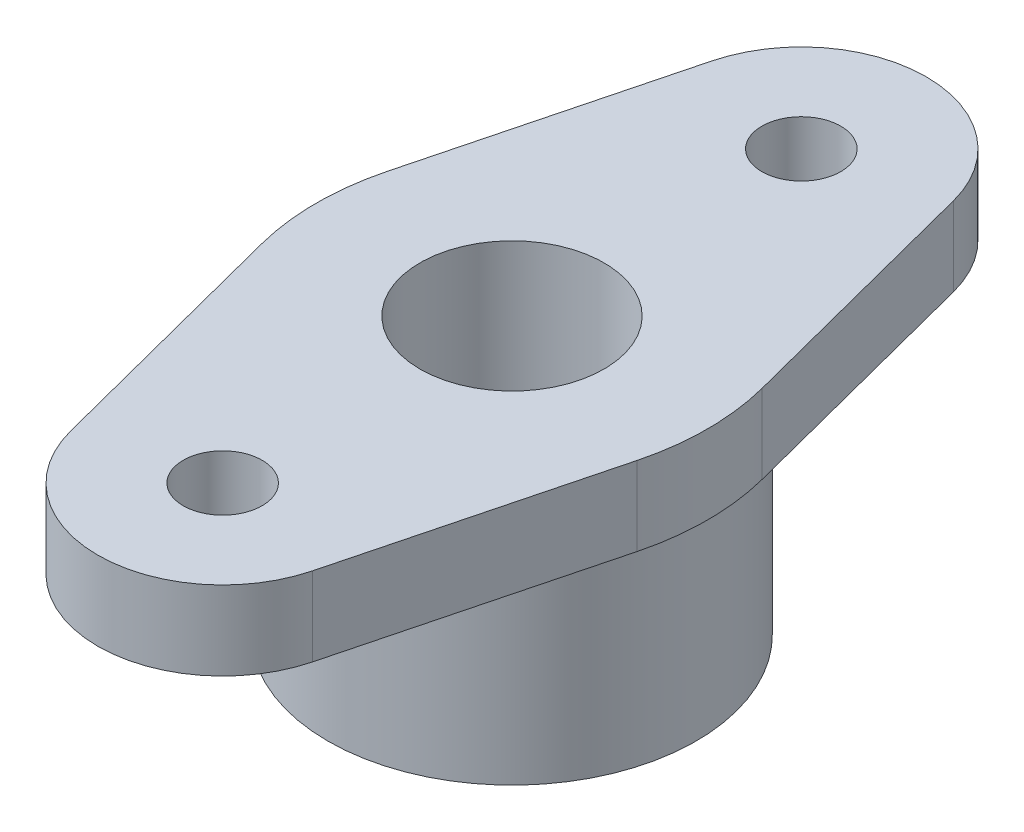
SolidWorks part; units mm, degrees
ref_plane "Front Plane" through (0, 0, 0) normal (0, 0, 1) x (1, 0, 0)
ref_plane "Top Plane" through (0, 0, 0) normal (0, 1, 0) x (1, 0, 0)
ref_plane "Right Plane" through (0, 0, 0) normal (1, 0, 0) x (0, 0, -1)
sketch "Sketch2" plane through (0, 0, 0) normal (0, 1, 0) x (1, 0, 0)
  line L0 (-31, 0) -> (31, 0) construction
  line L1 (0, 0) -> (0, 44) construction
  line L2 (18.3952, 48.7557) -> (31, 0)
  line L3 (31, 0) -> (18.3952, -48.7557)
  line L4 (-31, 0) -> (-18.3952, -48.7557)
  line L5 (-18.3952, 48.7557) -> (-31, 0)
  circle A0 centre (0, 44) radius 19
  circle A1 centre (0, 44) radius 6
  circle A2 centre (0, 0) radius 14
  circle A3 centre (0, -44) radius 6
  circle A4 centre (0, -44) radius 19
  dimension "D1" = 38
  dimension "D2" = 12
  dimension "D3" = 28
  dimension "D4" = 88
  dimension "D5" = 62
extrude "Boss-Extrude1" add sketch "Sketch2" along normal blind 12 contours L4 A4 L3 L2 A0 L5 A2 | A4 A3 | A0 A1
fillet "Fillet1" radius 38 2 edges at (-31, 6, 0) (31, 6, 0)
sketch "Sketch3" plane through (0, 0, 0) normal (0, 0, 1) x (1, 0, 0)
  line L0 (0, 0) -> (0, -41.4435) construction
  line L1 (14, 0) -> (28, 0)
  line L2 (-18.3952, 0) -> (18.3952, 0) construction
  line L3 (28.541, 0) -> (18.3952, 0) construction
  line L4 (28, 0) -> (28, -30)
  line L5 (14, 0) -> (14, -21.9171)
  line L6 (14, -21.9171) -> (28, -30)
  line L7 (14, 0) -> (14, 12) construction
  dimension "D1" = 30
  dimension "D2" = 28
  dimension "D3" = 60
revolve "Revolve1" add sketch "Sketch3" angle 360 about L0
